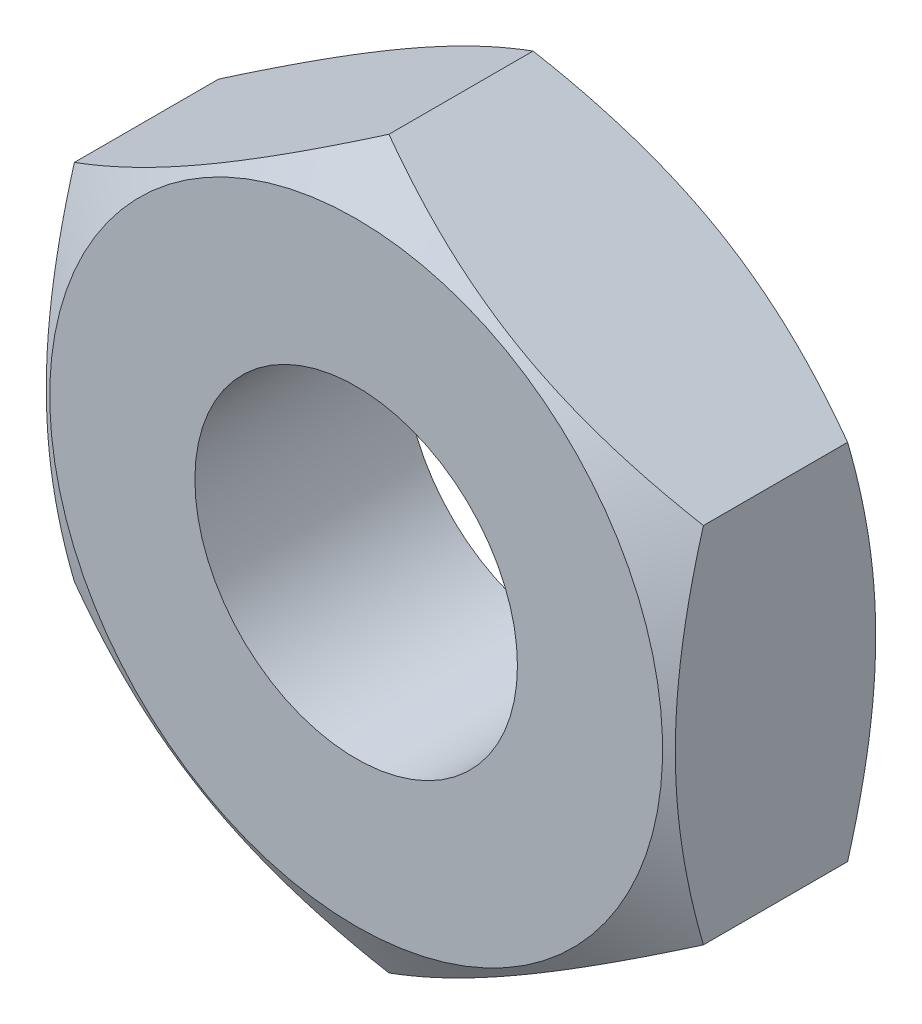
SolidWorks part; units mm, degrees
ref_plane "Спереди" through (0, 0, 0) normal (0, 0, 1) x (1, 0, 0)
ref_plane "Сверху" through (0, 0, 0) normal (0, 1, 0) x (1, 0, 0)
ref_plane "Справа" through (0, 0, 0) normal (1, 0, 0) x (0, 0, -1)
sketch "Sketch1" plane through (0, 0, 0) normal (0, 0, 1) x (1, 0, 0)
  line L7 (0, 2.2517) -> (-1.95, 1.1258)
  line L8 (-1.95, 1.1258) -> (-1.95, -1.1258)
  line L9 (-1.95, -1.1258) -> (0, -2.2517)
  line L10 (0, -2.2517) -> (1.95, -1.1258)
  line L11 (1.95, -1.1258) -> (1.95, 1.1258)
  line L12 (1.95, 1.1258) -> (0, 2.2517)
  circle A0 centre (0, 0) radius 1
  circle A1 centre (0, 0) radius 1.95 construction
extrude "Extrude1" add sketch "Sketch1" along normal blind 1.3
sketch "Sketch2" plane through (0, 0, 0) normal (1, 0, 0) x (0, 0, -1)
  line L0 (0, 1.9) -> (-0.7615, 3.219)
  line L1 (0, 1.9) -> (0, 5.1947)
  line L2 (-1.3, 0) -> (0, 0)
  line L3 (-1.3, -1.1258) -> (-1.3, 1.1258) construction
  line L4 (-0.65, 0) -> (-0.65, -3.3526) construction
  line L5 (-1.3, 1.9) -> (-1.3, 5.1947)
  line L6 (-1.3, 1.9) -> (-0.5385, 3.219)
  line L7 (-3.1638, 2.6533) -> (0.8049, 2.6533)
  circle A0 centre (0, 0) radius 1.9
  circle A1 centre (-1.3, 0) radius 1.9
revolve "Cut-Revolve1" cut sketch "Sketch2" angle 360 about L2
